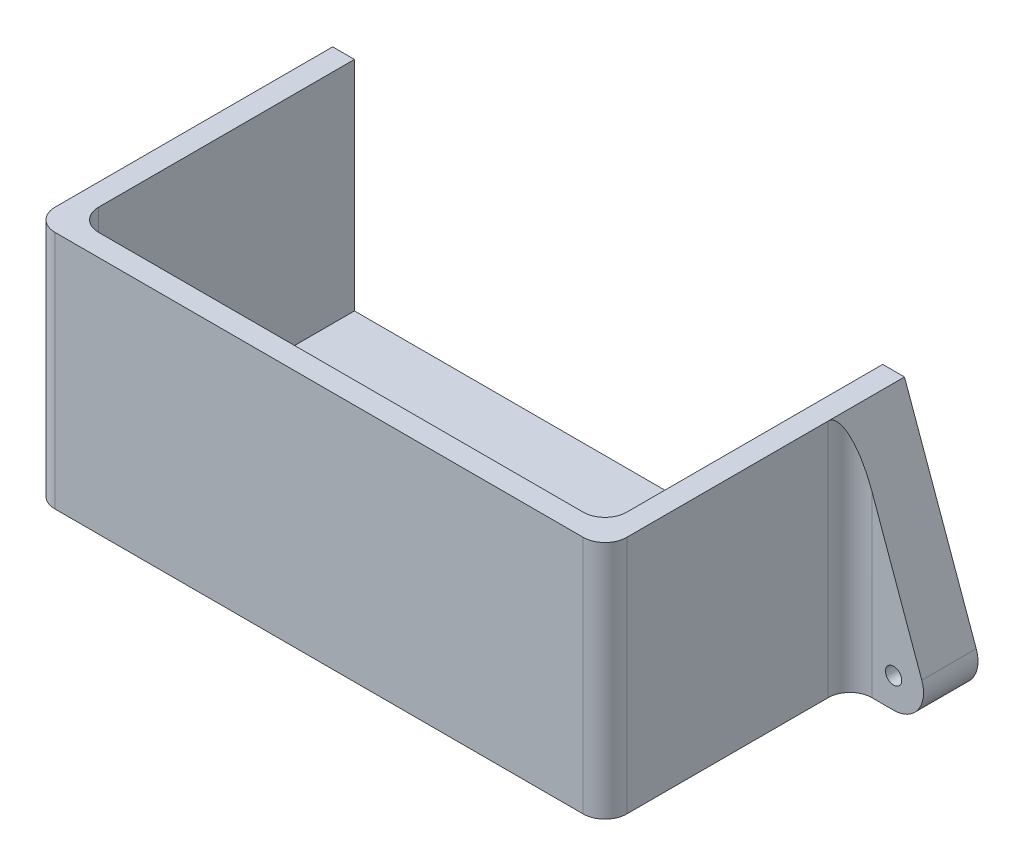
SolidWorks part; units mm, degrees
ref_plane "Front Plane" through (0, 0, 0) normal (0, 0, 1) x (1, 0, 0)
ref_plane "Top Plane" through (0, 0, 0) normal (0, 1, 0) x (1, 0, 0)
ref_plane "Right Plane" through (0, 0, 0) normal (1, 0, 0) x (0, 0, -1)
sketch "Sketch1" plane through (0, 0, 0) normal (0, 1, 0) x (1, 0, 0)
  line L0 (26.25, 12.75) -> (26.25, -14.75)
  line L1 (-24.25, 12.75) -> (24.25, 12.75) construction
  line L2 (-24.25, 12.75) -> (-24.25, -12.75) construction
  line L3 (-24.25, -12.75) -> (24.25, -12.75) construction
  line L4 (24.25, 12.75) -> (24.25, -12.75) construction
  line L5 (0, -12.75) -> (0, 12.75) construction
  line L6 (-24.25, 0) -> (24.25, 0) construction
  line L7 (-26.25, -14.75) -> (26.25, -14.75)
  line L8 (-26.25, 12.75) -> (-26.25, -14.75)
  line L9 (-26.25, 12.75) -> (26.25, 12.75)
  point P4 (0, 0)
  point P9 (27.5137, -15.0137)
  point P140 (0, 0)
  dimension "D1" = 25.5
  dimension "D2" = 48.5
  dimension "D3" = 2
  dimension "D4" = 2
extrude "Boss-Extrude1" add sketch "Sketch1" along normal blind 2
sketch "Sketch2" plane through (0, 2, 0) normal (0, 1, 0) x (1, 0, 0)
  line L8 (26.25, -14.75) -> (26.25, 12.75)
  line L9 (-26.25, -14.75) -> (26.25, -14.75)
  line L10 (-26.25, 12.75) -> (-26.25, -14.75)
  line L11 (26.25, 12.75) -> (-26.25, 12.75)
  line L12 (26.25, -14.75) -> (26.25, 12.75)
  line L13 (-26.25, -14.75) -> (26.25, -14.75)
  line L14 (-26.25, 12.75) -> (-26.25, -14.75)
  line L15 (26.25, 12.75) -> (24.25, 12.75)
  line L16 (-24.25, 12.75) -> (-24.25, -12.75)
  line L17 (-24.25, -12.75) -> (24.25, -12.75)
  line L18 (24.25, -12.75) -> (24.25, 12.75)
  line L19 (-24.25, 12.75) -> (-26.25, 12.75)
  dimension "D2" = 2
  dimension "D3" = 2
  dimension "D4" = 2
  dimension "D1" = 0
extrude "Boss-Extrude2" add sketch "Sketch2" along normal blind 20
fillet "Fillet1" radius 2 4 edges at (-26.25, 11, 14.75) (26.25, 11, 14.75) (24.25, 12, 12.75) (-24.25, 12, 12.75)
sketch "Sketch3" plane through (0, 0, -12.75) normal (0, 0, -1) x (-1, 0, 0)
  line L1 (-26.25, 22) -> (-26.25, 0) construction
  line L2 (-26.25, 22) -> (-32.8378, 3.6806)
  line L3 (-26.25, 0) -> (-30.25, 0)
  line L5 (-26.25, 0) -> (26.25, 0) construction
  line L6 (-26.25, 22) -> (-26.25, 0)
  line L7 (-26.25, 22) -> (-26.25, 0)
  arc A0 (-32.8378, 3.6806) -> (-30.25, 0) centre (-30.25, 2.75) ccw
  circle A1 centre (-30.25, 2.75) radius 0.75
  point P6 (0, 0)
  point P9 (-26.25, 22)
  point P10 (0, 0)
  point P12 (0, 0)
  point P13 (-26.25, 22)
  point P14 (0, 0)
  point P15 (0, 0)
  point P18 (0, 0)
  point P20 (-29.6685, 11)
  point P21 (-30.25, 3.653)
  point P22 (-30.2531, 2.7545)
  point P23 (-30.25, 3.4207)
  point P24 (-30.25, 5.4092)
  dimension "D1" = 1.5
  dimension "D2" = 2
  dimension "D4" = 4
  dimension "D3" = 0
extrude "Boss-Extrude3" add sketch "Sketch3" against normal blind 5
mirror "Mirror3" about plane through (0, 0, 0) normal (1, 0, 0) of "Boss-Extrude3"
fillet "Fillet3" radius 2 2 edges at (-26.25, 11, -7.75) (26.25, 11, -7.75)
